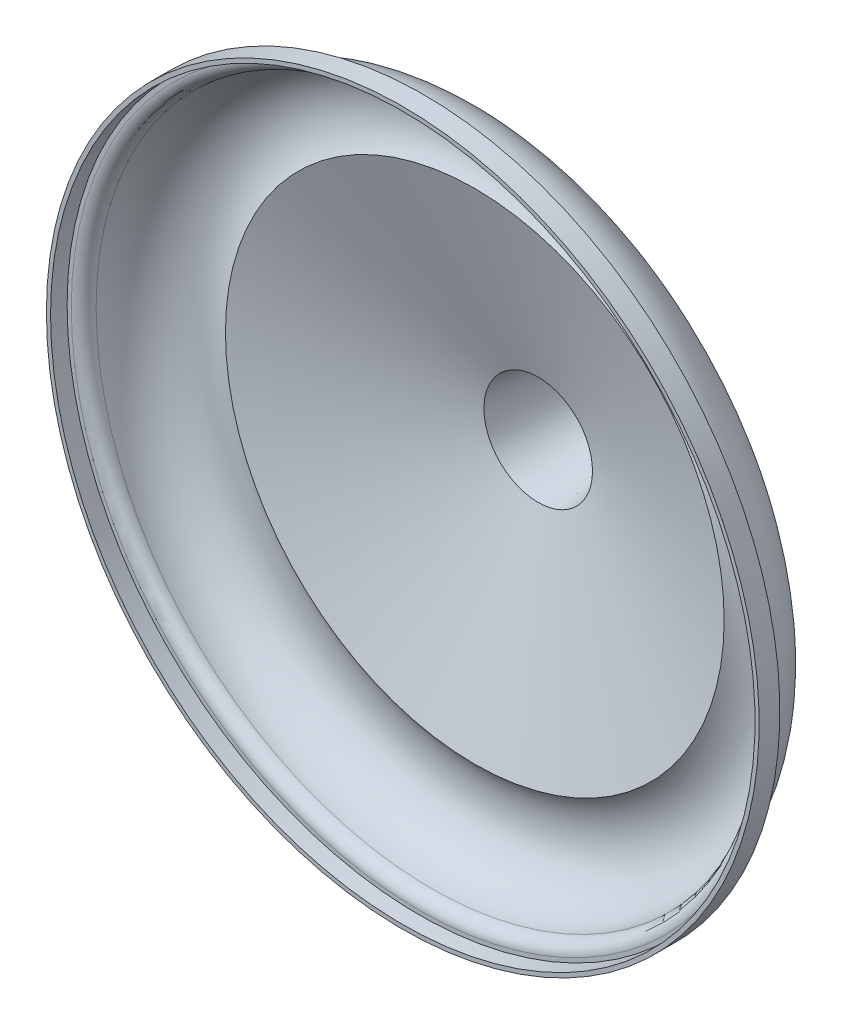
SolidWorks part; units mm, degrees
material "Plain Carbon Steel"
ref_plane "Front Plane" through (0, 0, 0) normal (0, 0, 1) x (1, 0, 0)
ref_plane "Top Plane" through (0, 0, 0) normal (0, 1, 0) x (1, 0, 0)
ref_plane "Right Plane" through (0, 0, 0) normal (1, 0, 0) x (0, 0, -1)
sketch "Sketch1" plane through (0, 0, 0) normal (0, 1, 0) x (1, 0, 0)
  line L0 (0, 30) -> (0, 0)
  line L1 (43, 2.5) -> (42, 2.5)
  line L2 (0, 0) -> (62.0628, 0) construction
  line L3 (30, 9.2446) -> (7, 16.7177)
  line L4 (43, 0) -> (0, 0)
  line L6 (41, 3.5) -> (41, 37.7928) construction
  line L7 (43, 0) -> (43, 2.5)
  line L8 (0, 10) -> (75.6092, 11.1136) construction
  line L14 (5.15, 29.3256) -> (7, 16.7177)
  arc A0 (41, 3.5) -> (30, 9.2446) centre (34, 3.5) ccw
  arc A1 (42, 2.5) -> (41, 3.5) centre (42, 3.5) cw
  arc A2 (5.15, 29.3256) -> (0, 30) centre (0, 10) ccw
  point P24 (7, 0)
  point P25 (7, 16.7177)
  point P26 (-7, 0)
  point P27 (0, 0)
  dimension "D6" = 7
  dimension "D7" = 1
  dimension "D8" = 10
  dimension "D13" = 20
  dimension "D2" = 5.15
  dimension "D3" = 30
  dimension "D4" = 34
  dimension "D5" = 2.5
  dimension "D11" = 43
  dimension "D9" = 41
  dimension "D10" = 18
  dimension "D12" = 7
revolve "Revolve2" add sketch "Sketch1" angle 360 about L0
shell "Shell1" thickness 0.5
